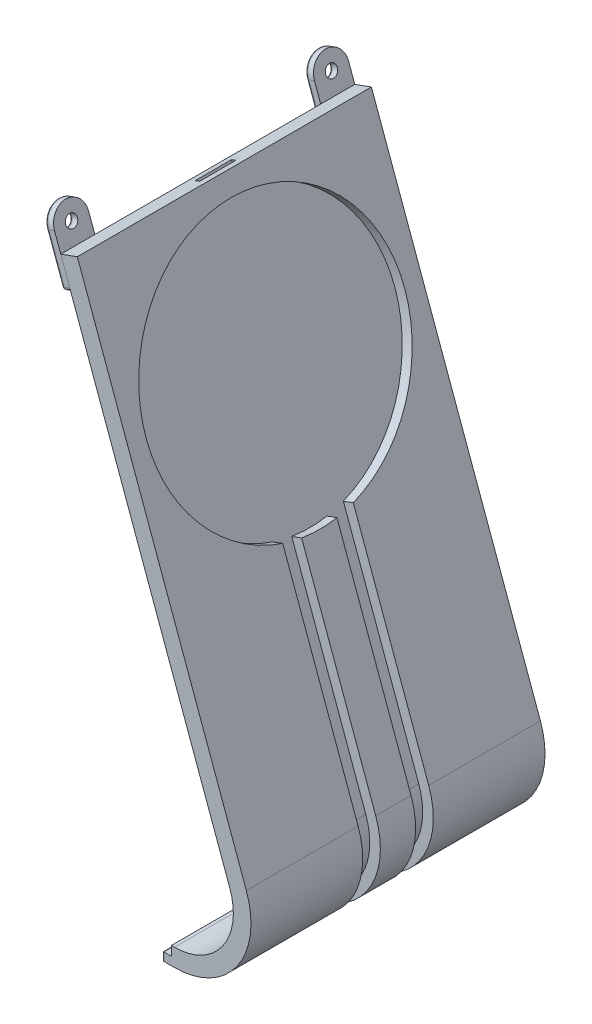
SolidWorks part; units mm, degrees
material "PLA"
ref_plane "前视基准面" through (0, 0, 0) normal (0, 0, 1) x (1, 0, 0)
ref_plane "上视基准面" through (0, 0, 0) normal (0, 1, 0) x (1, 0, 0)
ref_plane "右视基准面" through (0, 0, 0) normal (1, 0, 0) x (0, 0, -1)
other "Configuration Table"
sketch "草图2" plane through (0, 0, 0) normal (0, 0, 1) x (1, 0, 0)
  line L0 (-44.8208, 6.0497) -> (31.0025, 6.0497) construction
  line L5 (40.3995, 19.4699) -> (11.6565, 98.4406)
  line L6 (30.3692, 6.0497) -> (30.3692, 4.5497) construction
  line L7 (13.6945, 105.2907) -> (9.3719, 103.7174) construction
  line L8 (9.3719, 104.7174) -> (40.3995, 19.4699) construction
  line L12 (31.0025, 6.0497) -> (30.4692, 6.0497)
  arc A0 (31.0025, 6.0497) -> (40.3995, 19.4699) centre (31.0025, 16.0497) ccw
  arc A1 (31.0025, 6.0497) -> (40.3995, 19.4699) centre (31.0025, 16.0497) ccw construction
  dimension "D3" = 0.1
  dimension "D1" = 5.74
extrude "整体拉伸-薄壁1" add sketch "草图2" along normal mid plane 50 thin
sketch "草图4" plane through (44.7502, 16.2877, 0) normal (0.9397, 0.342, 0) x (0, 0, -1)
  line L0 (-25, 88.5171) -> (25, 88.5171) construction
  circle A0 centre (0, 63.1171) radius 22
  dimension "D1" = 44
  dimension "D2" = 25.4
extrude "中间圆切除-拉伸1" cut sketch "草图4" against normal blind 1.8
sketch "草图3" plane through (0, 0, 0) normal (0, 0, 1) x (1, 0, 0)
  line L0 (43.2186, 20.4959) -> (14.4756, 99.4666) construction
  line L1 (43.2186, 20.4959) -> (14.4756, 99.4666) construction
  line L2 (30.4692, 3.0497) -> (30.4692, 6.0497) construction
  line L5 (41.5271, 19.8803) -> (28.9959, 54.3095)
  line L6 (41.5271, 19.8803) -> (12.7841, 98.851) construction
  line L7 (30.4692, 4.8624) -> (30.4692, 4.8624) construction
  line L9 (28.9959, 54.3095) -> (30.6873, 54.9252) construction
  line L16 (28.9959, 54.3095) -> (27.9698, 57.1286)
  line L17 (28.672, 4.9619) -> (19.9046, 9.2795) construction
  arc A0 (31.0025, 6.0497) -> (40.3995, 19.4699) centre (31.0025, 16.0497) ccw construction
  arc A1 (19.9046, 9.2795) -> (43.2186, 20.4959) centre (31.0025, 16.0497) ccw construction
  arc A2 (30.4692, 4.8624) -> (41.5271, 19.8803) centre (31.0025, 16.0497) ccw
  dimension "D2" = 3
  dimension "D1" = 1.8
extrude "线槽切除-拉伸-薄壁1" cut sketch "草图3" against normal blind 3 from offset 6 thin
mirror "镜向1" about plane through (0, 0, 0) normal (0, 0, 1) of "线槽切除-拉伸-薄壁1"
sketch "草图11" plane through (30.4692, 0, 0) normal (-1, 0, 0) x (0, 0, 1)
  line L0 (-25, 3.0497) -> (-25, 6.0497) construction
  line L1 (-25, 4.4497) -> (-6, 4.4497)
  line L2 (-25, 4.4497) -> (-25, 3.0497)
  line L3 (-25, 3.0497) -> (-6, 3.0497)
  line L4 (-6, 4.4497) -> (-6, 3.0497)
  line L5 (-6, 4.8624) -> (-6, 3.0606) construction
  line L6 (6, 4.4497) -> (25, 4.4497)
  line L7 (6, 4.4497) -> (6, 3.0497)
  line L8 (6, 3.0497) -> (25, 3.0497)
  line L9 (25, 4.4497) -> (25, 3.0497)
  line L10 (25, 3.0497) -> (-25, 3.0497) construction
  line L11 (6, 3.0606) -> (6, 4.8624) construction
  line L12 (25, 3.0497) -> (25, 6.0497) construction
  line L14 (25, 6.0497) -> (-25, 6.0497) construction
  dimension "D1" = 1.6
  dimension "D2" = 1.6
extrude "底部卡扣凸台-拉伸3" add sketch "草图11" along normal blind 1.5
fillet "底部卡扣圆角1" radius 0.25 8 edges at (28.9692, 4.4497, 15.5) (28.9692, 3.7497, 25) (28.9692, 3.0497, 15.5) (28.9692, 3.7497, 6) (28.9692, 4.4497, -15.5) (28.9692, 3.7497, -6) (28.9692, 3.0497, -15.5) (28.9692, 3.7497, -25)
sketch "草图15" plane through (41.9311, 15.2617, 0) normal (-0.9397, -0.342, 0) x (0, 0, 1)
  line L5 (0, 95.1968) -> (0, 74.5538) construction
  line L6 (37.5, 95.1968) -> (-37.5, 95.1968) construction
  line L19 (-25, 4.4783) -> (-25, 88.5171) construction
  line L21 (-25, 91.6171) -> (-25, 83.5171)
  line L22 (-25, 83.5171) -> (-19.2, 83.5171)
  line L23 (-19.2, 91.6171) -> (-19.2, 83.5171)
  line L24 (25, 88.5171) -> (-25, 88.5171) construction
  line L25 (19.2, 91.6171) -> (19.2, 83.5171)
  line L26 (25, 83.5171) -> (19.2, 83.5171)
  line L27 (25, 91.6171) -> (25, 83.5171)
  arc A0 (-19.2, 91.6171) -> (-25, 91.6171) centre (-22.1, 91.6171) ccw
  circle A1 centre (-22.1, 91.6171) radius 1
  circle A6 centre (22.1, 91.6171) radius 1
  arc A7 (19.2, 91.6171) -> (25, 91.6171) centre (22.1, 91.6171) cw
  dimension "D1" = 2
  dimension "D2" = 5
extrude "螺丝凸台-拉伸1" add sketch "草图15" along normal blind 1.5 separate body
sketch "草图14" plane through (-30.2746, 83.1789, 0) normal (-0.342, 0.9397, 0) x (0.9397, 0.342, 0)
  line L0 (44.2802, -5.1) -> (47.2802, -5.1) construction
  line L1 (46.4222, 3.1) -> (45.6222, 3.1)
  line L2 (46.4222, 3.1) -> (46.4222, -3.1)
  line L3 (46.4222, -3.1) -> (45.6222, -3.1)
  line L4 (45.6222, 3.1) -> (45.6222, -3.1)
  line L5 (47.2802, 5.1) -> (44.2802, 5.1) construction
  line L6 (44.6222, -25) -> (44.6222, 25) construction
  line L7 (47.6222, -25) -> (47.6222, 25) construction
  dimension "D1" = 2
  dimension "D2" = 2
  dimension "D3" = 1
  dimension "D4" = 1.2
extrude "扣部切除-拉伸2" cut sketch "草图14" against normal blind 1
fillet "螺丝圆角2" radius 0.5 7 edges at (9.5287, 99.9009, -22.1) (8.1948, 103.5657, -22.1) (10.5719, 97.0348, -25) (10.5719, 97.0348, -19.2) (11.9571, 93.2291, -22.1) (12.6618, 93.4856, -19.2) (12.6618, 93.4856, -25)
fillet "螺丝圆角3" radius 0.5 7 edges at (8.8447, 101.7803, 22.1) (11.9571, 93.2291, 22.1) (10.5719, 97.0348, 19.2) (8.1948, 103.5657, 22.1) (12.6618, 93.4856, 19.2) (10.5719, 97.0348, 25) (12.6618, 93.4856, 25)
